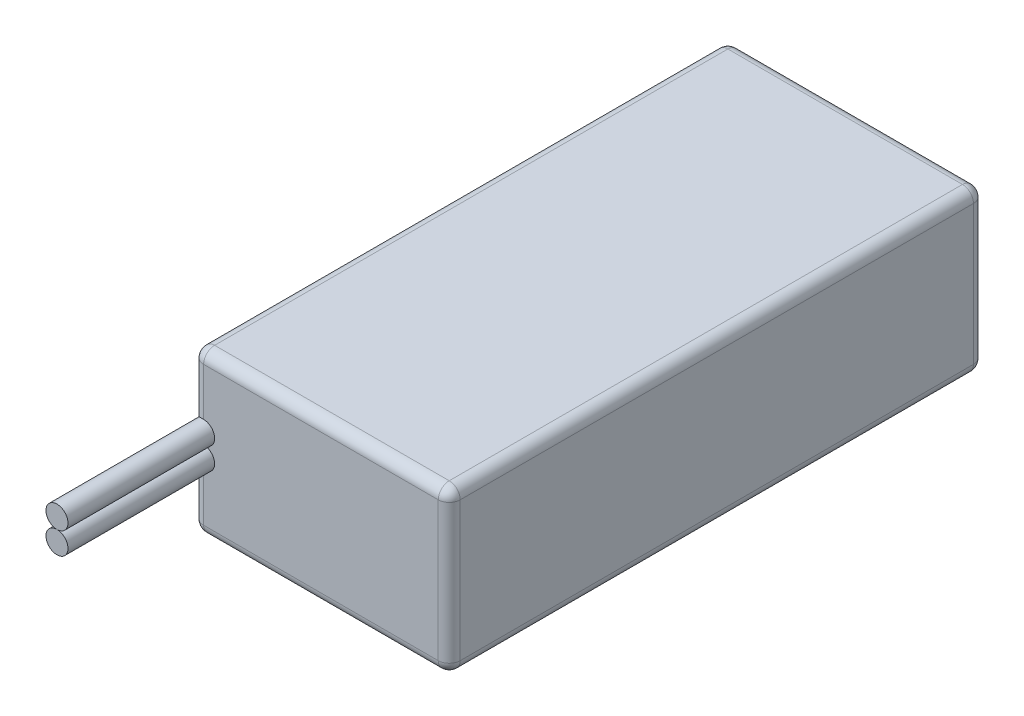
SolidWorks part; units mm, degrees
ref_plane "前基準面" through (0, 0, 0) normal (0, 0, 1) x (1, 0, 0)
ref_plane "上基準面" through (0, 0, 0) normal (0, 1, 0) x (1, 0, 0)
ref_plane "右基準面" through (0, 0, 0) normal (1, 0, 0) x (0, 0, -1)
sketch "Sketch1" plane through (0, 0, 0) normal (0, 1, 0) x (1, 0, 0)
  line L1 (-17.5, -36.5) -> (17.5, -36.5)
  line L2 (-17.5, -36.5) -> (-17.5, 36.5)
  line L3 (-17.5, 36.5) -> (17.5, 36.5)
  line L4 (17.5, -36.5) -> (17.5, 36.5)
  line L5 (0, 36.5) -> (0, -36.5) construction
  line L6 (-17.5, 0) -> (17.5, 0) construction
  point P0 (0, 0)
  dimension "D1" = 73
  dimension "D2" = 35
extrude "Boss-Extrude1" add sketch "Sketch1" along normal blind 22
fillet "Fillet1" radius 1.5 12 edges at (17.5, 11, -36.5) (-17.5, 11, -36.5) (-17.5, 11, 36.5) (17.5, 11, 36.5) (0, 22, 36.5) (-17.5, 22, 0) (0, 22, -36.5) (17.5, 22, 0) (0, 0, -36.5) (-17.5, 0, 0) (0, 0, 36.5) (17.5, 0, 0)
sketch "Sketch2" plane through (0, 0, 36.5) normal (0, 0, 1) x (1, 0, 0)
  line L0 (0, 0) -> (0, 22) construction
  line L1 (-16, 22) -> (16, 22) construction
  line L2 (0, 11) -> (-17.5, 11) construction
  line L3 (-17.5, 1.5) -> (-17.5, 20.5) construction
  circle A0 centre (-16, 12.5) radius 1.5
  circle A1 centre (-16, 9.5) radius 1.5
  line M6 (-16, 20.5) -> (-16, 1.5)
  dimension "D1" = 3
extrude "Boss-Extrude5" add sketch "Sketch2" along normal blind 20 and the other way blind 5 separate body contours A0 M6 | A0 M6 | A1 M6 | A1 M6
